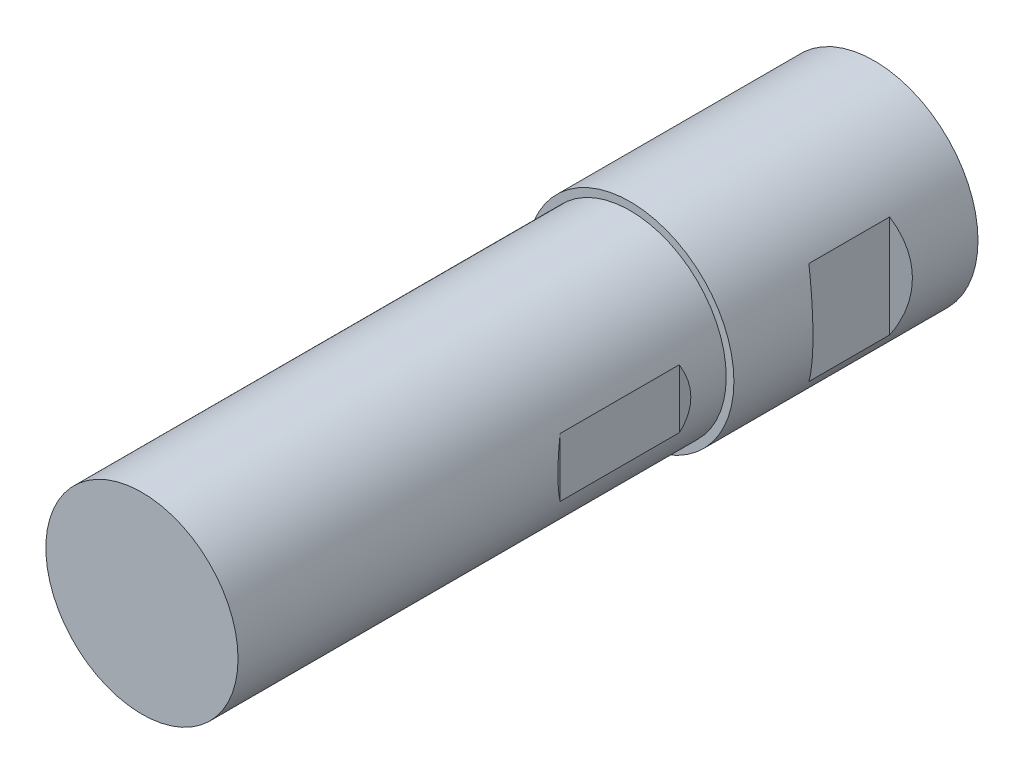
SolidWorks part; units mm, degrees
ref_plane "Front Plane" through (0, 0, 0) normal (0, 0, 1) x (1, 0, 0)
ref_plane "Top Plane" through (0, 0, 0) normal (0, 1, 0) x (1, 0, 0)
ref_plane "Right Plane" through (0, 0, 0) normal (1, 0, 0) x (0, 0, -1)
sketch "Sketch1" plane through (0, 0, 0) normal (0, 0, 1) x (1, 0, 0)
  circle A0 centre (0, 0) radius 27
  dimension "D1" = 54
extrude "Boss-Extrude1" add sketch "Sketch1" along normal blind 63.5
sketch "Sketch2" plane through (0, 0, 63.5) normal (0, 0, 1) x (1, 0, 0)
  circle A0 centre (0, 0) radius 25
  dimension "D1" = 50
extrude "Boss-Extrude2" add sketch "Sketch2" along normal blind 127
sketch "Sketch4" plane through (0, 0, 0) normal (0, 1, 0) x (1, 0, 0)
  line L0 (-25, -72.7112) -> (-23.8, -74.5)
  line L1 (-25, -63.5) -> (-25, -190.5) construction
  line L2 (-23.8, -74.5) -> (-23.8, -105.5)
  line L3 (-23.8, -90) -> (-56.0935, -90) construction
  line L4 (0, -190.5) -> (0, -39.6912) construction
  line L5 (-25, -190.5) -> (25, -190.5) construction
  line L6 (-25, -107.2888) -> (-23.8, -105.5)
  line L7 (25, -107.2888) -> (23.8, -105.5)
  line L8 (25, -72.7112) -> (23.8, -74.5)
  line L9 (23.8, -74.5) -> (23.8, -105.5)
  line L10 (-27.7579, -16.5329) -> (-23.5, -19.5)
  line L11 (-23.5, -19.5) -> (-23.5, -40.5)
  line L12 (-23.5, -30) -> (-45.4253, -30) construction
  line L13 (-27.7579, -43.4671) -> (-23.5, -40.5)
  line L14 (-25, -72.7112) -> (-25, -107.2888)
  line L15 (25, -107.2888) -> (25, -72.7112)
  line L16 (-27.7579, -16.5329) -> (-27.7579, -43.4671)
  line L17 (27.7579, -43.4671) -> (23.5, -40.5)
  line L18 (27.7579, -16.5329) -> (23.5, -19.5)
  line L19 (23.5, -19.5) -> (23.5, -40.5)
  line L20 (27.7579, -16.5329) -> (27.7579, -43.4671)
  line L21 (-27, -63.5) -> (27, -63.5) construction
  line L22 (-27, 0) -> (-27, -63.5) construction
  point P13 (0, 0)
  point P32 (0, 0)
  point P33 (-26.999, -13.5895)
  dimension "D1" = 31
  dimension "D2" = 85
  dimension "D3" = 47.6
  dimension "D4" = 47
  dimension "D5" = 23
  dimension "D6" = 21
extrude "Cut-Extrude1" cut sketch "Sketch4" against normal through all both and the other way through all contours L0 L14 L6 L2 | L16 L13 L11 L10 | L9 L7 L15 L8 | L20 L17 L19 L18
